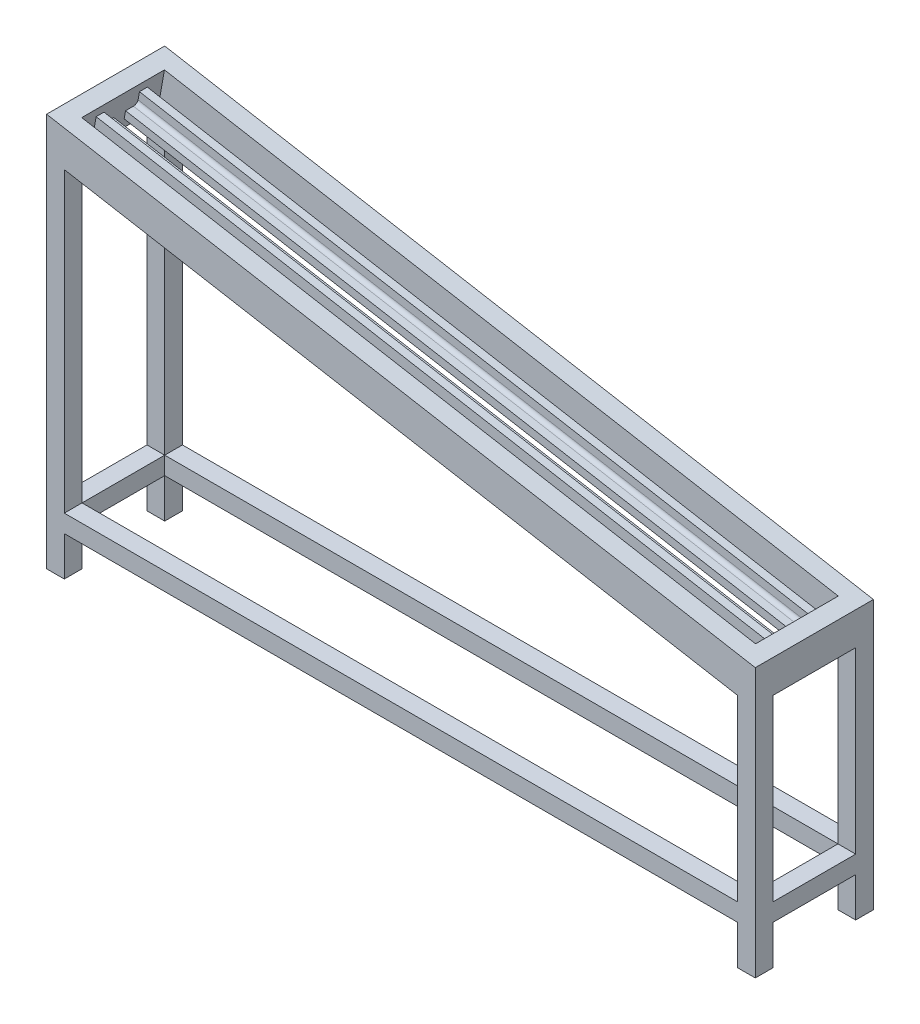
SolidWorks part; units mm, degrees
ref_plane "Plano frontal" through (0, 0, 0) normal (0, 0, 1) x (1, 0, 0)
ref_plane "Plano superior" through (0, 0, 0) normal (0, 1, 0) x (1, 0, 0)
ref_plane "Plano direito" through (0, 0, 0) normal (1, 0, 0) x (0, 0, -1)
sketch "Esboço1" plane through (0, 0, 0) normal (0, 0, 1) x (1, 0, 0)
  line L0 (0, 1000) -> (0, 0)
  line L1 (0, 0) -> (1800, 0)
  line L2 (1800, 0) -> (1800, 682.6114)
  line L3 (1800, 682.6114) -> (0, 1000)
  dimension "D1" = 1800
  dimension "D2" = 1000
  dimension "D3" = 80
extrude "Ressalto-extrusão1" add sketch "Esboço1" along normal blind 300
sketch "Esboço2" plane through (0, 0, 300) normal (0, 0, 1) x (1, 0, 0)
  line L0 (0, 0) -> (1800, 0) construction
  line L1 (45, 0) -> (1755, 0)
  line L2 (45, 0) -> (45, 100)
  line L3 (45, 100) -> (1755, 100)
  line L4 (1755, 0) -> (1755, 100)
  line L5 (45, 900.6769) -> (45, 145)
  line L6 (45, 145) -> (1755, 145)
  line L7 (1755, 145) -> (1755, 599.1578)
  line L8 (1755, 599.1578) -> (45, 900.6769)
  line L9 (1800, 682.6114) -> (0, 1000) construction
  line L10 (0, 1000) -> (0, 0) construction
  line L11 (1800, 0) -> (1800, 682.6114) construction
  dimension "D1" = 45
  dimension "D2" = 45
  dimension "D3" = 45
  dimension "D4" = 90
  dimension "D5" = 100
extrude "Corte-extrusão1" cut sketch "Esboço2" against normal up to surface (300 mm away) up to face at (900, 420.6529, 0)
sketch "Esboço3" plane through (1800, 0, 0) normal (1, 0, 0) x (0, 0, -1)
  line L0 (-300, 0) -> (0, 0) construction
  line L1 (-255, 0) -> (-45, 0)
  line L2 (-255, 0) -> (-255, 599.1578)
  line L3 (-255, 599.1578) -> (-45, 599.1578)
  line L4 (-45, 0) -> (-45, 599.1578)
  line L5 (0, 0) -> (0, 682.6114) construction
  line L7 (-300, 0) -> (-300, 682.6114) construction
  line L9 (-255, 145) -> (-45, 145)
  line L10 (-255, 145) -> (-255, 100)
  line L11 (-255, 100) -> (-45, 100)
  line L12 (-45, 145) -> (-45, 100)
  line M9 (-300, 0) -> (0, 0)
  dimension "D1" = 45
  dimension "D2" = 45
extrude "Corte-extrusão2" cut sketch "Esboço3" against normal up to vertex contours L2 L9 L4 L3 | L11 L2 L4 M9
sketch "Esboço4" plane through (0, 145, 0) normal (0, 1, 0) x (1, 0, 0)
  line L1 (45, -255) -> (1755, -255)
  line L2 (45, -255) -> (45, -45)
  line L3 (45, -45) -> (1755, -45)
  line L4 (1755, -255) -> (1755, -45)
extrude "Corte-extrusão3" cut sketch "Esboço4" against normal up to vertex (45 mm away)
sketch "Esboço5" plane through (45, 0, 0) normal (1, 0, 0) x (0, 0, -1)
  line L0 (0, 900.6769) -> (-300, 900.6769) construction
  line L1 (-255, 599.1578) -> (-45, 599.1578)
  line L2 (-255, 599.1578) -> (-255, 900.6769)
  line L3 (-255, 900.6769) -> (-45, 900.6769)
  line L4 (-45, 599.1578) -> (-45, 900.6769)
  line L6 (0, 145) -> (0, 900.6769) construction
  dimension "D1" = 45
extrude "Corte-extrusão4" cut sketch "Esboço5" against normal up to surface (45 mm away) up to face at (0, 275, 150)
sketch "Esboço6" plane through (171.0101, 969.8463, 0) normal (0.1736, 0.9848, 0) x (0.9848, -0.1736, 0)
  line L0 (1654.1197, -300) -> (-173.6482, -300) construction
  line L1 (-128.6482, -255) -> (1609.1197, -255)
  line L2 (-128.6482, -255) -> (-128.6482, -45)
  line L3 (-128.6482, -45) -> (1609.1197, -45)
  line L4 (1609.1197, -255) -> (1609.1197, -45)
  line L5 (1654.1197, 0) -> (-173.6482, 0) construction
  line L6 (1654.1197, -300) -> (1654.1197, 0) construction
  line L7 (-173.6482, -300) -> (-173.6482, 0) construction
  dimension "D1" = 45
  dimension "D2" = 45
  dimension "D3" = 45
  dimension "D4" = 45
extrude "Corte-extrusão5" cut sketch "Esboço6" against normal blind 150
sketch "Esboço8" plane through (-126.6937, 22.3395, 0) normal (0.9848, -0.1736, 0) x (0, 0, -1)
  line L0 (-215, 964.8078) -> (-215, 914.8078)
  line L1 (-215, 914.8078) -> (-165, 914.8078)
  line L2 (-165, 914.8078) -> (-165, 934.8078)
  line L3 (-165, 934.8078) -> (-195, 934.8078)
  line L4 (-195, 934.8078) -> (-195, 964.8078)
  line L5 (-195, 964.8078) -> (-215, 964.8078)
  line L6 (-135, 914.8078) -> (-85, 914.8078)
  line L7 (-85, 914.8078) -> (-85, 964.8078)
  line L8 (-85, 964.8078) -> (-105, 964.8078)
  line L9 (-105, 964.8078) -> (-105, 934.8078)
  line L10 (-105, 934.8078) -> (-135, 934.8078)
  line L11 (-135, 934.8078) -> (-135, 914.8078)
  line L12 (-45, 984.8078) -> (-255, 984.8078) construction
  line L13 (-150, 984.8078) -> (-150, 891.8871) construction
  line L14 (-45, 891.8871) -> (-255, 891.8871) construction
  dimension "D1" = 20
  dimension "D2" = 20
  dimension "D3" = 50
  dimension "D4" = 50
  dimension "D5" = 30
  dimension "D6" = 20
extrude "Ressalto-extrusão2" add sketch "Esboço8" along normal up to surface (1737.7679 mm away) up to face at (1747.8695, 646.1093, 150)
fillet "Filete1" radius 10 2 edges at (891.3176, 792.0653, 105) (891.3176, 792.0653, 195)
